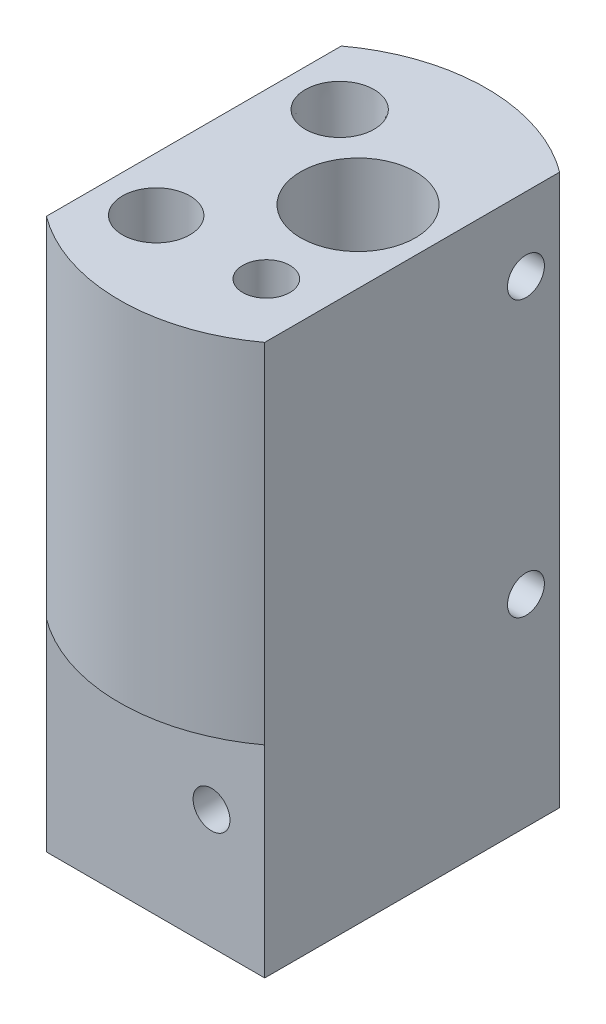
SolidWorks part; units mm, degrees
ref_plane "Front Plane" through (0, 0, 0) normal (0, 0, 1) x (1, 0, 0)
ref_plane "Top Plane" through (0, 0, 0) normal (0, 1, 0) x (1, 0, 0)
ref_plane "Right Plane" through (0, 0, 0) normal (1, 0, 0) x (0, 0, -1)
sketch "Sketch2" plane through (0, 0, 0) normal (0, 1, 0) x (1, 0, 0)
  circle A0 centre (0, 0) radius 25.4
  dimension "D1" = 50.8
extrude "Cylinder Base" add sketch "Sketch2" along normal blind 76.2
sketch "Sketch3" plane through (0, 76.2, 0) normal (0, 1, 0) x (1, 0, 0)
  line L2 (-15.1144, 20.4136) -> (-15.1144, -20.4136)
  line L3 (15.1144, 20.4136) -> (15.1144, -20.4136)
  circle A0 centre (0, 0) radius 25.4 construction
  arc A1 (-15.1144, 20.4136) -> (-15.1144, -20.4136) centre (0, 0) ccw
  arc A2 (15.1144, 20.4136) -> (15.1144, -20.4136) centre (0, 0) cw
extrude "Side Trim" cut sketch "Sketch3" against normal blind 76.2
sketch "Sketch4" plane through (0, 76.2, 0) normal (0, 1, 0) x (1, 0, 0)
  line L0 (-15.1144, 0) -> (15.1144, 0)
  line L1 (-15.1144, -20.4136) -> (-15.1144, 20.4136) construction
  line L2 (15.1144, 20.4136) -> (15.1144, -20.4136) construction
  line L3 (0, 25.4) -> (0, -25.4)
  arc A0 (15.1144, 20.4136) -> (-15.1144, 20.4136) centre (0, 0) ccw construction
  arc A1 (-15.1144, -20.4136) -> (15.1144, -20.4136) centre (0, 0) ccw construction
  circle A2 centre (5.08, 2.54) radius 7.9375
  dimension "D1" = 15.875
  dimension "D2" = 2.54
  dimension "D3" = 5.08
extrude "Main Hole" cut sketch "Sketch4" against normal blind 63.5 contours L0 A2 L3 | L3 A2 L0 | L3 A2 L0 | L0 A2 L3
sketch "Sketch11" plane through (0, 76.2, 0) normal (0, 1, 0) x (1, 0, 0)
  line L0 (-15.1144, 0) -> (15.1144, 0)
  line L1 (-15.1144, -20.4136) -> (-15.1144, 20.4136) construction
  line L2 (15.1144, 20.4136) -> (15.1144, -20.4136) construction
  line L3 (0, 25.4) -> (0, -25.4)
  arc A0 (15.1144, 20.4136) -> (-15.1144, 20.4136) centre (0, 0) ccw construction
  arc A1 (-15.1144, -20.4136) -> (15.1144, -20.4136) centre (0, 0) ccw construction
  circle A2 centre (-7.62, 12.7) radius 4.2164
  dimension "D1" = 8.4328
  dimension "D2" = 7.62
  dimension "D3" = 12.7
hole_wizard "1/8 NPT Tapped Hole4" positions "3DSketch3" profile "Sketch14" size "1/8" standard "ANSI Inch"
sketch3d "3DSketch3"
  point P0 (-7.62, 76.2, -12.7)
sketch "Sketch14" plane through (-7.62, 76.2, -12.7) normal (1, 0, 0) x (0, 0, 1)
  line L0 (0, 0) -> (0, 20.32)
  line L1 (4.2164, 17.7865) -> (0, 20.32)
  line L2 (-4.2164, 17.7865) -> (0, 20.32) construction
  line L3 (4.2164, 17.7865) -> (4.2164, 7.62)
  line L4 (4.2164, 7.62) -> (4.5374, 7.62)
  line L5 (4.5374, 7.62) -> (4.7656, 0)
  line L6 (-4.5374, 7.62) -> (-4.7656, 0) construction
  line L7 (4.7656, 0) -> (0, 0)
  line L8 (0, -6.35) -> (0, 107.95) construction
  line L11 (-4.2164, 7.62) -> (-4.5374, 7.62) construction
  dimension "Tap Drill Dia." = 8.4328
  dimension "Tap Drill Depth" = 20.32
  dimension "Thread Dia." = 9.5311
  dimension "Thread Angle" = 3.43
  dimension "Thread Depth" = 7.62
  dimension "Drill Angle" = 118
cosmetic thread "Hole Thread1" parameters "D1"=7.62, "D2"=10.3287
sketch "Sketch15" plane through (0, 76.2, 0) normal (0, 1, 0) x (1, 0, 0)
  line L0 (-15.1144, 0) -> (15.1144, 0) construction
  line L1 (0, 25.4) -> (0, -25.4) construction
  circle A0 centre (-7.62, -12.7) radius 4.6736
  dimension "D1" = 9.3472
  dimension "D2" = 12.7
  dimension "D3" = 7.62
hole_wizard "7/16-14 Tapped Hole1" positions "3DSketch4" profile "Sketch16" tap size "7/16-14" standard "ANSI Inch"
sketch3d "3DSketch4"
  point P0 (-7.62, 76.2, 12.7)
sketch "Sketch16" plane through (-7.62, 76.2, 12.7) normal (1, 0, 0) x (0, 0, 1)
  line L0 (0, 0) -> (0, 22.352)
  line L1 (0, 22.352) -> (4.6736, 19.5438)
  line L2 (4.6736, 19.5438) -> (4.6736, 0)
  line L5 (4.6736, 0) -> (0, 0)
  line L10 (0, 22.352) -> (-4.6736, 19.5438) construction
  line L11 (0, -6.35) -> (0, 107.95) construction
  dimension "Tap Drill Dia." = 9.3472
  dimension "Tap Drill Depth" = 22.352
  dimension "Drill Angle" = 118
cosmetic thread "Hole Thread2" parameters "D1"=19.5438, "D2"=11.1125
sketch "Sketch17" plane through (0, 76.2, 0) normal (0, 1, 0) x (1, 0, 0)
  line L0 (-15.1144, 0) -> (15.1144, 0) construction
  line L1 (0, 25.4) -> (0, -25.4) construction
  circle A0 centre (7.62, -12.7) radius 3.2639
  dimension "D1" = 6.5278
  dimension "D2" = 12.7
  dimension "D3" = 7.62
hole_wizard "5/16-18 Tapped Hole1" positions "3DSketch5" profile "Sketch18" tap size "5/16-18" standard "ANSI Inch"
sketch3d "3DSketch5"
  point P0 (7.62, 76.2, 12.7)
sketch "Sketch18" plane through (7.62, 76.2, 12.7) normal (1, 0, 0) x (0, 0, 1)
  line L0 (0, 0) -> (0, 10.16)
  line L1 (0, 10.16) -> (3.2639, 8.1989)
  line L2 (3.2639, 8.1989) -> (3.2639, 0)
  line L5 (3.2639, 0) -> (0, 0)
  line L10 (0, 10.16) -> (-3.2639, 8.1989) construction
  line L11 (0, -6.35) -> (0, 107.95) construction
  dimension "Tap Drill Dia." = 6.5278
  dimension "Tap Drill Depth" = 10.16
  dimension "Drill Angle" = 118
cosmetic thread "Hole Thread3" parameters "D1"=8.1989, "D2"=7.9375
sketch "Sketch19" plane through (0, 76.2, 0) normal (0, 1, 0) x (1, 0, 0)
  circle A0 centre (-7.62, 12.7) radius 3.175
  dimension "D1" = 6.35
extrude "Cut-Extrude3" cut sketch "Sketch19" against normal blind 63.5
sketch "Sketch20" plane through (0, 76.2, 0) normal (0, 1, 0) x (1, 0, 0)
  circle A0 centre (-7.62, 12.7) radius 4.2164
  dimension "D1" = 8.4328
extrude "Cut-Extrude4" cut sketch "Sketch20" against normal blind 45.72
sketch "Sketch21" plane through (0, 76.2, 0) normal (0, 1, 0) x (1, 0, 0)
  circle A0 centre (-7.62, -12.7) radius 3.175
  dimension "D1" = 6.35
extrude "Cut-Extrude5" cut sketch "Sketch21" against normal blind 63.5
sketch "Sketch22" plane through (0, 76.2, 0) normal (0, 1, 0) x (1, 0, 0)
  circle A0 centre (-7.62, -12.7) radius 4.6736
  dimension "D1" = 9.3472
extrude "Cut-Extrude6" cut sketch "Sketch22" against normal blind 45.72
sketch "Sketch23" plane through (0, 76.2, 0) normal (0, 1, 0) x (1, 0, 0)
  circle A0 centre (7.62, -12.7) radius 3.175
  dimension "D1" = 6.35
extrude "Cut-Extrude7" cut sketch "Sketch23" against normal blind 63.5
sketch "Sketch25" plane through (0, 76.2, 0) normal (0, 1, 0) x (1, 0, 0)
  circle A0 centre (7.62, -12.7) radius 3.2639
  dimension "D1" = 6.5278
extrude "Cut-Extrude9" cut sketch "Sketch25" against normal blind 14.478
sketch "Sketch26" plane through (-15.1144, 0, 0) normal (-1, 0, 0) x (0, 0, 1)
  line L0 (20.4136, 0) -> (20.4136, 76.2) construction
  line L1 (20.4136, 0) -> (-20.4136, 0) construction
  circle A0 centre (12.2856, 44.45) radius 2.5527
  dimension "D1" = 5.1054
  dimension "D2" = 8.128
  dimension "D3" = 44.45
hole_wizard "1/4-20 Tapped Hole2" positions "3DSketch7" profile "Sketch30" tap size "1/4-20" standard "ANSI Inch"
sketch3d "3DSketch7"
  point P0 (-15.1144, 44.45, 12.2856)
sketch "Sketch30" plane through (-15.1144, 44.45, 12.2856) normal (0, 1, 0) x (0, 0, 1)
  line L0 (0, 0) -> (0, 12.7)
  line L1 (0, 12.7) -> (2.5527, 11.1662)
  line L2 (2.5527, 11.1662) -> (2.5527, 0)
  line L5 (2.5527, 0) -> (0, 0)
  line L10 (0, 12.7) -> (-2.5527, 11.1662) construction
  line L11 (0, -6.35) -> (0, 107.95) construction
  dimension "Tap Drill Dia." = 5.1054
  dimension "Tap Drill Depth" = 12.7
  dimension "Drill Angle" = 118
cosmetic thread "Hole Thread5" parameters "D1"=11.1662, "D2"=6.35
sketch "Sketch31" plane through (-15.1144, 0, 0) normal (-1, 0, 0) x (0, 0, 1)
  circle A0 centre (12.2856, 44.45) radius 2.5527
  dimension "D1" = 5.1054
extrude "Cut-Extrude11" cut sketch "Sketch31" against normal blind 25.4
sketch "Sketch32" plane through (-15.1144, 0, 0) normal (-1, 0, 0) x (0, 0, 1)
  line L0 (20.4136, 0) -> (-20.4136, 0) construction
  circle A0 centre (-10.5744, 15.24) radius 2.5527
  dimension "D1" = 5.1054
  dimension "D2" = 15.24
  dimension "D3" = 22.86
hole_wizard "1/4-20 Tapped Hole3" positions "3DSketch8" profile "Sketch33" tap size "1/4-20" standard "ANSI Inch"
sketch3d "3DSketch8"
  point P0 (-15.1144, 15.24, -10.5744)
sketch "Sketch33" plane through (-15.1144, 15.24, -10.5744) normal (0, 1, 0) x (0, 0, 1)
  line L0 (0, 0) -> (0, 16.51)
  line L1 (0, 16.51) -> (2.5527, 14.9762)
  line L2 (2.5527, 14.9762) -> (2.5527, 0)
  line L5 (2.5527, 0) -> (0, 0)
  line L10 (0, 16.51) -> (-2.5527, 14.9762) construction
  line L11 (0, -6.35) -> (0, 107.95) construction
  dimension "Tap Drill Dia." = 5.1054
  dimension "Tap Drill Depth" = 16.51
  dimension "Drill Angle" = 118
cosmetic thread "Hole Thread6" parameters "D1"=12.7, "D2"=6.35
sketch "Sketch34" plane through (-15.1144, 0, 0) normal (-1, 0, 0) x (0, 0, 1)
  circle A0 centre (-10.5744, 15.24) radius 2.5527
  dimension "D1" = 5.1054
extrude "Cut-Extrude12" cut sketch "Sketch34" against normal blind 25.4
sketch "Sketch35" plane through (-15.1144, 0, 0) normal (-1, 0, 0) x (0, 0, 1)
  line L0 (20.4136, 0) -> (-20.4136, 0) construction
  circle A0 centre (12.2856, 15.24) radius 2.5527
  dimension "D1" = 5.1054
  dimension "D2" = 22.86
  dimension "D3" = 15.24
extrude "Cut-Extrude13" cut sketch "Sketch35" against normal blind 12.7
sketch "Sketch36" plane through (0, 0, 0) normal (0, -1, 0) x (1, 0, 0)
  line L0 (-15.1144, 20.4136) -> (15.1144, 20.4136)
  arc A0 (-15.1144, 20.4136) -> (15.1144, 20.4136) centre (0, 0) cw
extrude "Cut-Extrude14" cut sketch "Sketch36" against normal blind 27.94
sketch "Sketch37" plane through (0, 0, 20.4136) normal (0, 0, 1) x (1, 0, 0)
  line L0 (15.1144, 0) -> (15.1144, 27.94) construction
  line L1 (-15.1144, 0) -> (15.1144, 0) construction
  circle A0 centre (7.7484, 16.51) radius 2.5527
  dimension "D1" = 5.1054
  dimension "D2" = 7.366
  dimension "D3" = 16.51
hole_wizard "1/4-20 Tapped Hole4" positions "3DSketch10" profile "Sketch39" tap size "1/4-20" standard "ANSI Inch"
sketch3d "3DSketch10"
  point P0 (7.7484, 16.51, 20.4136)
sketch "Sketch39" plane through (7.7484, 16.51, 20.4136) normal (1, 0, 0) x (0, -1, 0)
  line L0 (0, 0) -> (0, 11.43)
  line L1 (0, 11.43) -> (2.5527, 9.8962)
  line L2 (2.5527, 9.8962) -> (2.5527, 0)
  line L5 (2.5527, 0) -> (0, 0)
  line L10 (0, 11.43) -> (-2.5527, 9.8962) construction
  line L11 (0, -6.35) -> (0, 107.95) construction
  dimension "Tap Drill Dia." = 5.1054
  dimension "Tap Drill Depth" = 11.43
  dimension "Drill Angle" = 118
cosmetic thread "Hole Thread7" parameters "D1"=9.8962, "D2"=6.35
sketch "Sketch40" plane through (0, 0, 20.4136) normal (0, 0, 1) x (1, 0, 0)
  circle A0 centre (7.7484, 16.51) radius 2.5527
  dimension "D1" = 5.1054
extrude "Cut-Extrude15" cut sketch "Sketch40" against normal blind 25.4
sketch "Sketch41" plane through (15.1144, 0, 0) normal (1, 0, 0) x (0, 0, -1)
  line L0 (25.4, 0) -> (25.4, 76.2) construction
  line L1 (20.4136, 0) -> (-20.4136, 0) construction
  circle A0 centre (15.748, 66.04) radius 2.5527
  dimension "D1" = 5.1054
  dimension "D2" = 9.652
  dimension "D3" = 66.04
hole_wizard "1/4-20 Tapped Hole5" positions "3DSketch11" profile "Sketch42" tap size "1/4-20" standard "ANSI Inch"
sketch3d "3DSketch11"
  point P0 (15.1144, 66.04, -15.748)
sketch "Sketch42" plane through (15.1144, 66.04, -15.748) normal (0, 1, 0) x (0, 0, -1)
  line L0 (0, 0) -> (0, 10.16)
  line L1 (0, 10.16) -> (2.5527, 8.6262)
  line L2 (2.5527, 8.6262) -> (2.5527, 0)
  line L5 (2.5527, 0) -> (0, 0)
  line L10 (0, 10.16) -> (-2.5527, 8.6262) construction
  line L11 (0, -6.35) -> (0, 107.95) construction
  dimension "Tap Drill Dia." = 5.1054
  dimension "Tap Drill Depth" = 10.16
  dimension "Drill Angle" = 118
cosmetic thread "Hole Thread8" parameters "D1"=8.6262, "D2"=6.35
sketch "Sketch43" plane through (15.1144, 0, 0) normal (1, 0, 0) x (0, 0, -1)
  circle A0 centre (15.748, 66.04) radius 2.5527
  dimension "D1" = 5.1054
extrude "Cut-Extrude16" cut sketch "Sketch43" against normal blind 13.462
sketch "Sketch44" plane through (15.1144, 0, 0) normal (1, 0, 0) x (0, 0, -1)
  line L0 (25.4, 0) -> (25.4, 76.2) construction
  line L1 (20.4136, 0) -> (-20.4136, 0) construction
  circle A0 centre (15.748, 27.94) radius 2.5527
  dimension "D1" = 5.1054
  dimension "D2" = 9.652
  dimension "D3" = 27.94
hole_wizard "1/4-20 Tapped Hole6" positions "3DSketch12" profile "Sketch45" tap size "1/4-20" standard "ANSI Inch"
sketch3d "3DSketch12"
  point P0 (15.1144, 27.94, -15.748)
sketch "Sketch45" plane through (15.1144, 27.94, -15.748) normal (0, 1, 0) x (0, 0, -1)
  line L0 (0, 0) -> (0, 10.16)
  line L1 (0, 10.16) -> (2.5527, 8.6262)
  line L2 (2.5527, 8.6262) -> (2.5527, 0)
  line L5 (2.5527, 0) -> (0, 0)
  line L10 (0, 10.16) -> (-2.5527, 8.6262) construction
  line L11 (0, -6.35) -> (0, 107.95) construction
  dimension "Tap Drill Dia." = 5.1054
  dimension "Tap Drill Depth" = 10.16
  dimension "Drill Angle" = 118
cosmetic thread "Hole Thread9" parameters "D1"=8.6262, "D2"=6.35
sketch "Sketch46" plane through (15.1144, 0, 0) normal (1, 0, 0) x (0, 0, -1)
  circle A0 centre (15.748, 27.94) radius 2.5527
  dimension "D1" = 5.1054
extrude "Cut-Extrude17" cut sketch "Sketch46" against normal blind 13.462
